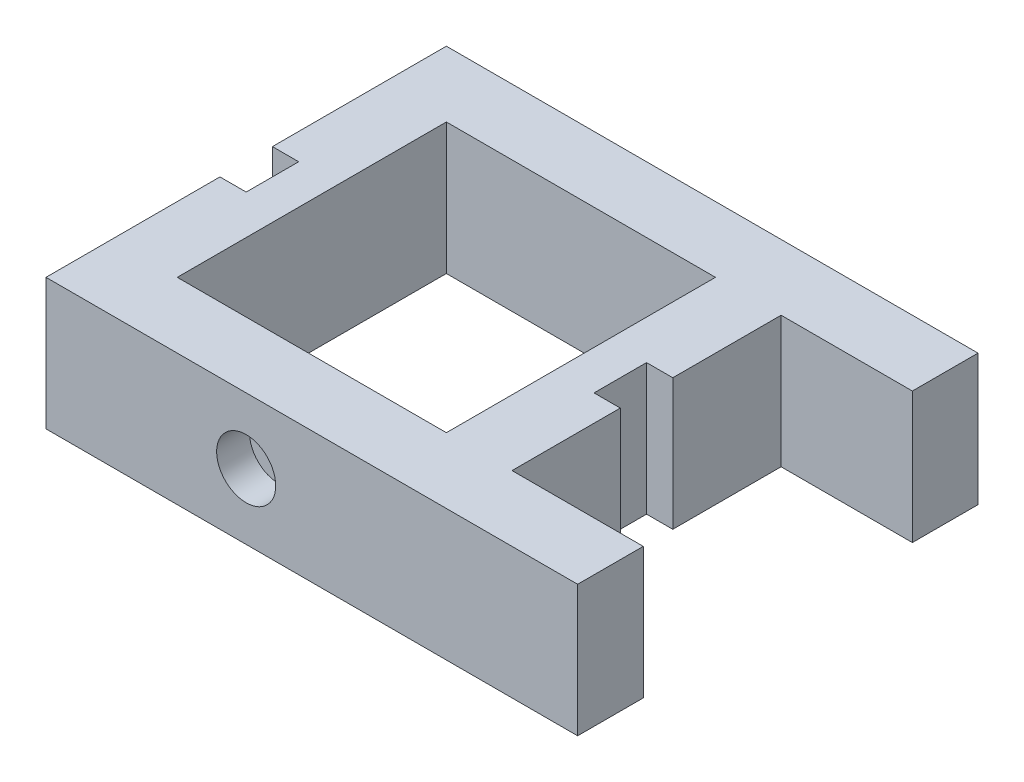
SolidWorks part; units mm, degrees
ref_plane "Ön Düzlem" through (0, 0, 0) normal (0, 0, 1) x (1, 0, 0)
ref_plane "Üst Düzlem" through (0, 0, 0) normal (0, 1, 0) x (1, 0, 0)
ref_plane "Sağ Düzlem" through (0, 0, 0) normal (1, 0, 0) x (0, 0, -1)
sketch "Sketch1" plane through (0, 0, 0) normal (0, 1, 0) x (1, 0, 0)
  line L5 (-41, 20.5) -> (0, 20.5)
  line L6 (-41, 20.5) -> (-41, -20.5)
  line L7 (-41, -20.5) -> (0, -20.5)
  line L8 (0, 20.5) -> (0, -20.5)
  line L9 (-51, 30.5) -> (10, 30.5)
  line L10 (-51, 30.5) -> (-51, 4)
  line L11 (-51, -30.5) -> (10, -30.5)
  line L12 (10, 20.5) -> (10, 4)
  line L13 (-47, 4) -> (-51, 4)
  line L14 (-47, 4) -> (-47, -4)
  line L15 (-47, -4) -> (-51, -4)
  line L21 (10, 30.5) -> (30, 30.5)
  line L23 (10, 20.5) -> (30, 20.5)
  line L24 (30, 30.5) -> (30, 20.5)
  line L28 (10, -4) -> (10, -20.5)
  line L29 (10, -20.5) -> (30, -20.5)
  line L31 (10, -30.5) -> (30, -30.5)
  line L32 (30, -20.5) -> (30, -30.5)
  line L33 (6, 4) -> (10, 4)
  line L34 (6, 4) -> (6, -4)
  line L35 (6, -4) -> (10, -4)
  line L37 (-51, -4) -> (-51, -30.5)
  point P4 (0, 0)
  dimension "D1" = 41
  dimension "D2" = 61
  dimension "D3" = 10
  dimension "D4" = 10
  dimension "D5" = 8
  dimension "D6" = 4
  dimension "D7" = 41
  dimension "D8" = 10
  dimension "D9" = 20
  dimension "D10" = 10
  dimension "D11" = 10
  dimension "D12" = 20
  dimension "D13" = 20
  dimension "D14" = 8
  dimension "D15" = 4
  dimension "D16" = 26.5
  dimension "D17" = 26.5
extrude "Boss-Extrude1" add sketch "Sketch1" along normal blind 20
sketch "Sketch2" plane through (0, 0, 30.5) normal (0, 0, 1) x (1, 0, 0)
  line L0 (-51, 20) -> (30, 20) construction
  line L1 (-51, 20) -> (-51, 0) construction
  circle A0 centre (-20.5, 10) radius 2.5
  dimension "D1" = 5
  dimension "D2" = 10
  dimension "D3" = 30.5
extrude "Cut-Extrude1" cut sketch "Sketch2" against normal blind 40
sketch "Sketch3" plane through (0, 0, 30.5) normal (0, 0, 1) x (1, 0, 0)
  circle A0 centre (-20.5, 10) radius 4.5
  dimension "D1" = 9
extrude "Cut-Extrude2" cut sketch "Sketch3" against normal blind 5
